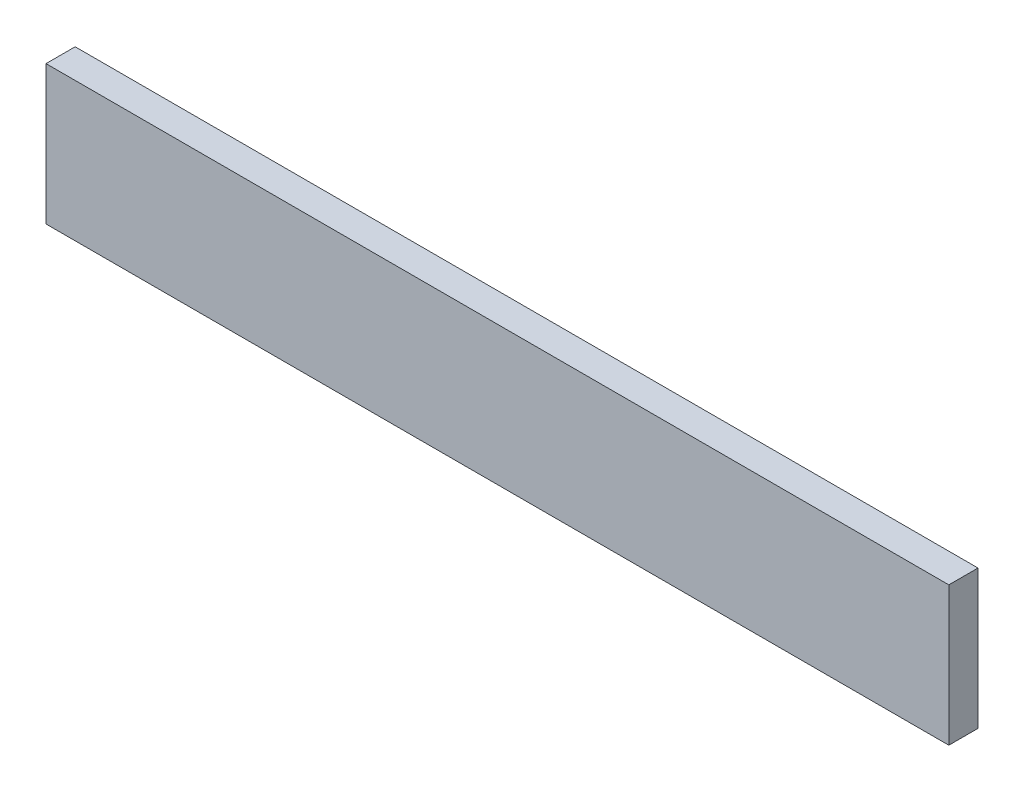
SolidWorks part; units mm, degrees
ref_plane "Front Plane" through (0, 0, 0) normal (0, 0, 1) x (1, 0, 0)
ref_plane "Top Plane" through (0, 0, 0) normal (0, 1, 0) x (1, 0, 0)
ref_plane "Right Plane" through (0, 0, 0) normal (1, 0, 0) x (0, 0, -1)
sketch "Sketch1" plane through (0, 0, 0) normal (0, 0, 1) x (1, 0, 0)
  line L1 (0, 0) -> (165.1, 0)
  line L2 (0, 0) -> (0, 25.4)
  line L3 (0, 25.4) -> (165.1, 25.4)
  line L4 (165.1, 0) -> (165.1, 25.4)
  dimension "D1" = 25.4
  dimension "D2" = 165.1
extrude "Boss-Extrude1" add sketch "Sketch1" along normal mid plane 5.334
equation "\"material\"= \"GMaterial@MotorizedPlatform.assembly\""
equation "\"D1@Boss-Extrude1\" = \"material\""
